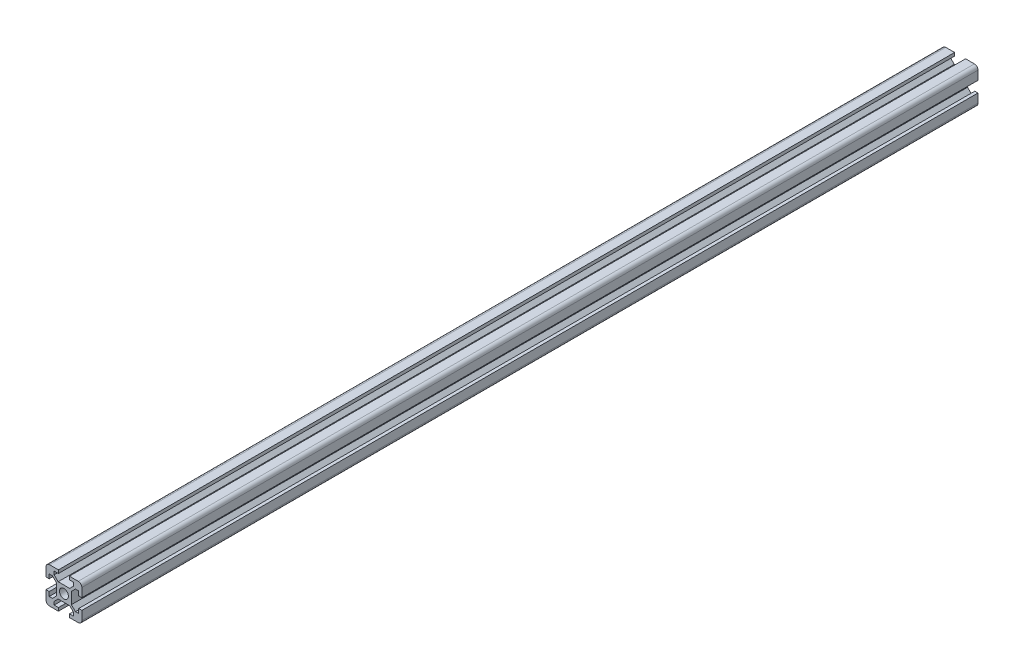
SolidWorks part; units mm, degrees
material "1060 Alloy"
ref_plane "Front Plane" through (0, 0, 0) normal (0, 0, 1) x (1, 0, 0)
ref_plane "Top Plane" through (0, 0, 0) normal (0, 1, 0) x (1, 0, 0)
ref_plane "Right Plane" through (0, 0, 0) normal (1, 0, 0) x (0, 0, -1)
sketch "Sketch1" plane through (0, 0, 0) normal (0, 0, 1) x (1, 0, 0)
  line L0 (-5.46, -6.42) -> (-3.215, -4.175)
  line L1 (-10, -10) -> (-3.06, -10)
  line L2 (-10, -10) -> (-10, -3.06)
  line L3 (-10, 10) -> (-3.06, 10)
  line L4 (10, -10) -> (10, -3.06)
  line L5 (-10, -10) -> (10, 10) construction
  line L6 (-10, 10) -> (10, -10) construction
  line L7 (-3.215, -4.175) -> (3.215, -4.175)
  line L8 (-4.175, -3.215) -> (-4.175, 3.215)
  line L9 (-3.215, 4.175) -> (3.215, 4.175)
  line L10 (4.175, -3.215) -> (4.175, 3.215)
  line L11 (-4.175, -4.175) -> (4.175, 4.175) construction
  line L12 (-4.175, 4.175) -> (4.175, -4.175) construction
  line L13 (-5.46, 6.42) -> (-5.46, 8.22)
  line L14 (-5.46, 8.22) -> (-3.06, 8.22)
  line L15 (-3.06, 8.22) -> (-3.06, 10)
  line L16 (-6.42, -5.46) -> (-4.175, -3.215)
  line L17 (5.46, 6.42) -> (5.46, 8.22)
  line L18 (5.46, 8.22) -> (3.06, 8.22)
  line L19 (3.06, 8.22) -> (3.06, 10)
  line L20 (-5.46, 6.42) -> (-3.215, 4.175)
  line L21 (6.42, 5.46) -> (8.22, 5.46)
  line L22 (8.22, 5.46) -> (8.22, 3.06)
  line L23 (8.22, 3.06) -> (10, 3.06)
  line L24 (8.22, -5.46) -> (6.42, -5.46)
  line L25 (-6.42, 5.46) -> (-4.175, 3.215)
  line L26 (8.22, -5.46) -> (8.22, -3.06)
  line L27 (8.22, -3.06) -> (10, -3.06)
  line L28 (5.46, 6.42) -> (3.215, 4.175)
  line L29 (5.46, -6.42) -> (5.46, -8.22)
  line L30 (5.46, -8.22) -> (3.06, -8.22)
  line L31 (3.06, -8.22) -> (3.06, -10)
  line L32 (6.42, 5.46) -> (4.175, 3.215)
  line L33 (-6.42, 5.46) -> (-8.22, 5.46)
  line L34 (-8.22, 5.46) -> (-8.22, 3.06)
  line L35 (-8.22, 3.06) -> (-10, 3.06)
  line L36 (6.42, -5.46) -> (4.175, -3.215)
  line L37 (-6.42, -5.46) -> (-8.22, -5.46)
  line L38 (-8.22, -5.46) -> (-8.22, -3.06)
  line L39 (-8.22, -3.06) -> (-10, -3.06)
  line L40 (5.46, -6.42) -> (3.215, -4.175)
  line L41 (-5.46, -6.42) -> (-5.46, -8.22)
  line L42 (-5.46, -8.22) -> (-3.06, -8.22)
  line L43 (-3.06, -8.22) -> (-3.06, -10)
  line L44 (-10, 3.06) -> (-10, 10)
  line L45 (3.06, 10) -> (10, 10)
  line L46 (10, 3.06) -> (10, 10)
  line L47 (3.06, -10) -> (10, -10)
  circle A0 centre (0, 0) radius 2.5
  point P0 (0, 0)
  dimension "D3" = 5
  dimension "D1" = 20
  dimension "D2" = 20
  dimension "D4" = 8.35
  dimension "D5" = 8.35
  dimension "D6" = 6.94
  dimension "D7" = 1.78
  dimension "D8" = 2.4
  dimension "D9" = 1.8
extrude "Boss-Extrude1" add sketch "Sketch1" along normal blind 500
fillet "Fillet1" radius 2 4 edges at (-10, -10, 250) (10, -10, 250) (-10, 10, 250) (10, 10, 250)
ref_plane "Plane1" through (0, 0, 250) normal (0, 0, 1) x (1, 0, 0)
